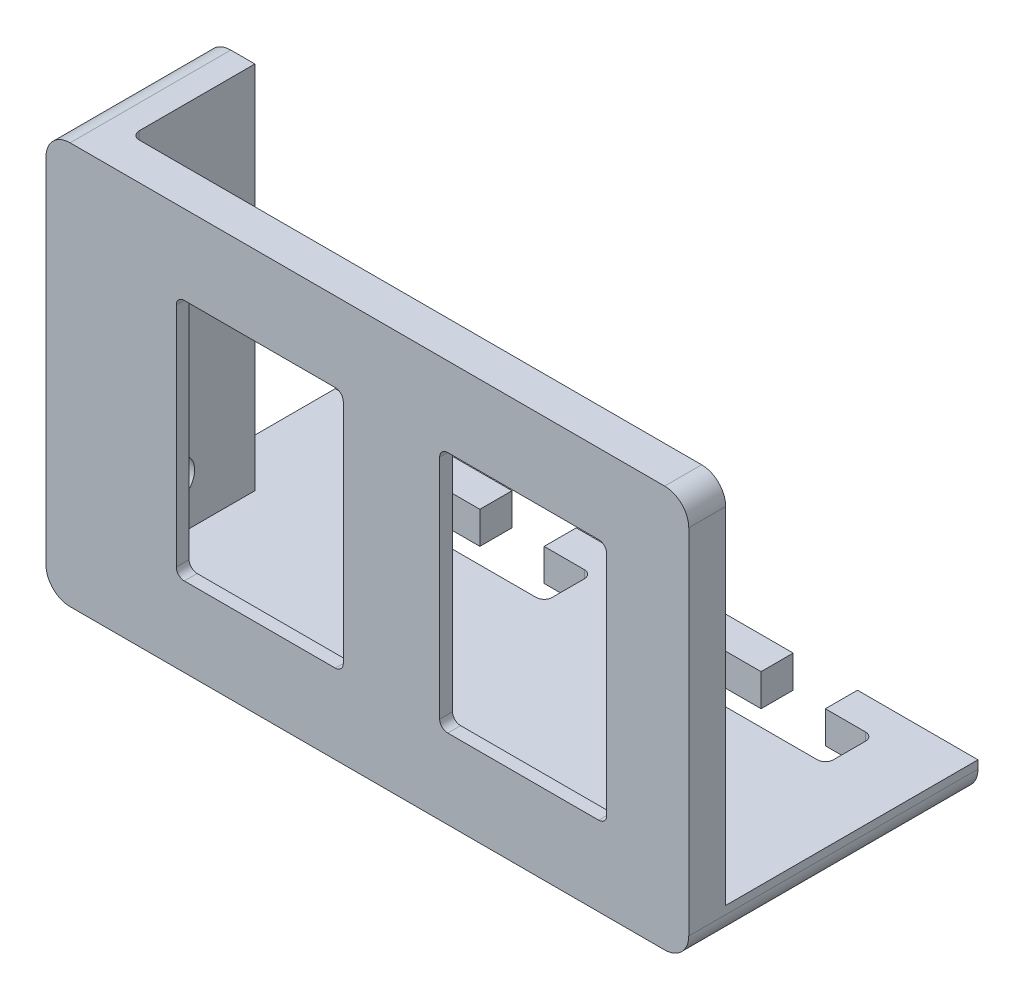
SolidWorks part; units mm, degrees
material "PLA2"
ref_plane "Front Plane" through (0, 0, 0) normal (0, 0, 1) x (1, 0, 0)
ref_plane "Top Plane" through (0, 0, 0) normal (0, 1, 0) x (1, 0, 0)
ref_plane "Right Plane" through (0, 0, 0) normal (1, 0, 0) x (0, 0, -1)
sketch "Sketch1" plane through (0, 0, 0) normal (0, 1, 0) x (1, 0, 0)
  line L0 (0, 0) -> (0, 12.7)
  line L1 (0, 12.7) -> (3.81, 12.7)
  line L2 (3.81, 12.7) -> (3.81, 2.921)
  line L3 (3.81, 2.921) -> (50.8, 2.921)
  line L4 (50.8, 2.921) -> (50.8, 0)
  line L5 (50.8, 0) -> (0, 0)
  dimension "D1" = 3.81
  dimension "D2" = 2.921
  dimension "D3" = 12.7
  dimension "D4" = 46.99
extrude "Boss-Extrude1" add sketch "Sketch1" along normal mid plane 31.75
sketch "Sketch2" plane through (3.81, 0, 0) normal (1, 0, 0) x (0, 0, -1)
  line L0 (12.7, 0) -> (0, 0) construction
  line L1 (12.7, 15.875) -> (12.7, -15.875) construction
  line L2 (6.35, 0) -> (6.35, 9.525) construction
  circle A0 centre (6.35, 9.525) radius 1.5875
  circle A1 centre (6.35, -9.525) radius 1.5875
  dimension "D1" = 3.175
  dimension "D2" = 19.05
extrude "Mounting_Holes" cut sketch "Sketch2" against normal through all
sketch "Sketch3" plane through (0, 0, -2.921) normal (0, 0, -1) x (-1, 0, 0)
  line L0 (-27.305, 15.875) -> (-27.305, -15.875) construction
  line L1 (-50.8, 15.875) -> (-3.81, 15.875) construction
  line L2 (-50.8, -15.875) -> (-3.81, -15.875) construction
  line L3 (-10.295, 0) -> (-23.495, 0) construction
  line L5 (-44.315, 9.6) -> (-44.315, -9.6)
  line L6 (-23.495, 9.6) -> (-10.295, 9.6)
  line L7 (-23.495, 9.6) -> (-23.495, -9.6)
  line L8 (-23.495, -9.6) -> (-10.295, -9.6)
  line L9 (-10.295, 9.6) -> (-10.295, -9.6)
  line L10 (-31.115, -9.6) -> (-44.315, -9.6)
  line L11 (-31.115, 9.6) -> (-31.115, -9.6)
  line L12 (-31.115, 9.6) -> (-44.315, 9.6)
  line L13 (-23.495, 0) -> (-27.305, 0) construction
  dimension "D1" = 13.2
  dimension "D2" = 19.2
  dimension "D4" = 3.81
extrude "Cut-Extrude2" cut sketch "Sketch3" against normal through all
sketch "Sketch4" plane through (0, 0, -2.921) normal (0, 0, -1) x (-1, 0, 0)
  line L0 (-10.295, 9.6) -> (-23.495, 9.6) construction
  line L1 (-10.295, -9.6) -> (-10.295, 9.6) construction
  line L2 (-23.495, -9.6) -> (-10.295, -9.6) construction
  line L3 (-23.495, 9.6) -> (-23.495, -9.6) construction
  line L4 (-44.315, -9.6) -> (-31.115, -9.6) construction
  line L5 (-31.115, -9.6) -> (-31.115, 9.6) construction
  line L6 (-31.115, 9.6) -> (-44.315, 9.6) construction
  line L7 (-44.315, 9.6) -> (-44.315, -9.6) construction
  line L8 (-10.295, 9.6) -> (-23.495, 9.6)
  line L9 (-10.295, -9.6) -> (-10.295, 9.6)
  line L10 (-23.495, -9.6) -> (-10.295, -9.6)
  line L11 (-23.495, 9.6) -> (-23.495, -9.6)
  line L12 (-44.315, -9.6) -> (-31.115, -9.6)
  line L13 (-31.115, -9.6) -> (-31.115, 9.6)
  line L14 (-31.115, 9.6) -> (-44.315, 9.6)
  line L15 (-44.315, 9.6) -> (-44.315, -9.6)
  line L16 (-44.315, 0) -> (-31.115, 0) construction
  line L17 (-37.715, 9.6) -> (-37.715, -9.6) construction
  line L18 (-3.81, 0) -> (-50.8, 0) construction
  line L19 (-46.855, 12.14) -> (-28.575, 12.14)
  line L20 (-46.855, 12.14) -> (-46.855, -12.14)
  line L21 (-46.855, -12.14) -> (-28.575, -12.14)
  line L22 (-28.575, 12.14) -> (-28.575, -12.14)
  line L23 (-46.855, 12.14) -> (-28.575, -12.14) construction
  line L24 (-46.855, -12.14) -> (-28.575, 12.14) construction
  line L25 (-3.81, 15.875) -> (-3.81, -15.875) construction
  line L26 (-50.8, 15.875) -> (-50.8, -15.875) construction
  line L27 (-27.305, 0) -> (-27.305, 15.875) construction
  line L28 (-50.8, 15.875) -> (-3.81, 15.875) construction
  line L29 (-7.755, -12.14) -> (-26.035, -12.14)
  line L30 (-26.035, 12.14) -> (-26.035, -12.14)
  line L31 (-7.755, 12.14) -> (-26.035, 12.14)
  line L32 (-7.755, 12.14) -> (-7.755, -12.14)
  point P12 (-37.715, 0)
  dimension "D1" = 2.54
  dimension "D2" = 2.54
extrude "Cut-Extrude3" cut sketch "Sketch4" against normal blind 1.905
fillet "Fillet2" radius 0.635 9 edges at (44.315, -9.6, -0.508) (31.115, -9.6, -0.508) (31.115, 9.6, -0.508) (44.315, 9.6, -0.508) (23.495, 9.6, -0.508) (23.495, -9.6, -0.508) (10.295, 9.6, -0.508) (10.295, -9.6, -0.508) (3.81, 0, -2.921)
fillet "Fillet3" radius 0.635 15 edges at (26.035, -12.14, -1.9685) (16.895, -12.14, -1.016) (7.755, -12.14, -1.9685) (7.755, 0, -1.016) (16.895, 12.14, -1.016) (7.755, 12.14, -1.9685) (26.035, 0, -1.016) (26.035, 12.14, -1.9685) (46.855, 12.14, -1.9685) (46.855, 0, -1.016) (46.855, -12.14, -1.9685) (37.715, -12.14, -1.016) (28.575, 0, -1.016) (37.715, 12.14, -1.016) (28.575, 12.14, -1.9685)
sketch "Sketch5" plane through (0, -15.875, 0) normal (0, -1, 0) x (1, 0, 0)
  line L0 (50.8, 0) -> (50.8, -22.86)
  line L1 (50.8, -22.86) -> (41.275, -22.86)
  line L2 (0, -12.7) -> (0, 0) construction
  line L3 (0, -22.86) -> (0, 0)
  line L4 (0, 0) -> (50.8, 0)
  line L5 (13.97, -22.86) -> (13.97, -20.32)
  line L6 (13.97, -20.32) -> (10.16, -20.32)
  line L7 (10.16, -20.32) -> (10.16, -16.51)
  line L8 (10.16, -16.51) -> (22.86, -16.51)
  line L9 (22.86, -16.51) -> (22.86, -20.32)
  line L10 (22.86, -20.32) -> (19.05, -20.32)
  line L11 (19.05, -20.32) -> (19.05, -22.86)
  line L12 (27.6225, -2.921) -> (27.6225, -22.86) construction
  line L13 (50.8, -2.921) -> (4.445, -2.921) construction
  line L14 (36.195, -20.32) -> (36.195, -22.86)
  line L15 (32.385, -20.32) -> (36.195, -20.32)
  line L16 (32.385, -16.51) -> (32.385, -20.32)
  line L17 (45.085, -16.51) -> (32.385, -16.51)
  line L18 (45.085, -20.32) -> (45.085, -16.51)
  line L19 (41.275, -20.32) -> (45.085, -20.32)
  line L20 (41.275, -22.86) -> (41.275, -20.32)
  line L21 (13.97, -22.86) -> (0, -22.86)
  line L22 (36.195, -22.86) -> (19.05, -22.86)
  line L23 (3.81, -3.556) -> (3.81, -12.7) construction
  line L24 (3.81, -12.7) -> (0, -12.7) construction
  dimension "D1" = 5.08
  dimension "D2" = 12.7
  dimension "D3" = 2.54
  dimension "D4" = 2.54
  dimension "D5" = 3.81
  dimension "D6" = 10.16
  dimension "0.3" = 10.16
extrude "Boss-Extrude3" add sketch "Sketch5" against normal blind 2.54
fillet "Fillet4" radius 0.635 8 edges at (10.16, -14.605, -20.32) (22.86, -14.605, -20.32) (22.86, -14.605, -16.51) (10.16, -14.605, -16.51) (45.085, -14.605, -20.32) (32.385, -14.605, -20.32) (32.385, -14.605, -16.51) (45.085, -14.605, -16.51)
fillet "Fillet5" radius 1.905 4 edges at (0, 15.875, -6.35) (0, -15.875, -11.43) (50.8, -15.875, -11.43) (50.8, 15.875, -1.4605)
